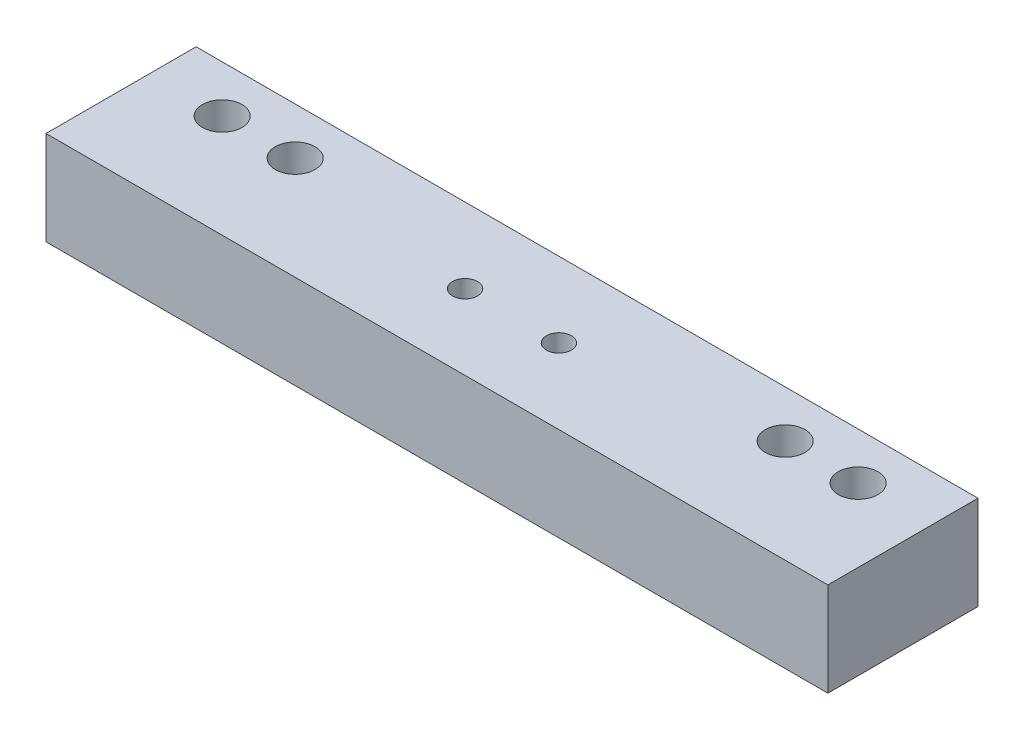
SolidWorks part; units mm, degrees
ref_plane "Front" through (0, 0, 0) normal (0, 0, 1) x (1, 0, 0)
ref_plane "Top" through (0, 0, 0) normal (0, 1, 0) x (1, 0, 0)
ref_plane "Right" through (0, 0, 0) normal (1, 0, 0) x (0, 0, -1)
sketch "Sketch1" plane through (0, 0, 0) normal (0, 1, 0) x (1, 0, 0)
  line L1 (0, 0) -> (125, 0)
  line L2 (0, 0) -> (0, 24)
  line L3 (0, 24) -> (125, 24)
  line L4 (125, 0) -> (125, 24)
  dimension "D1" = 125
  dimension "D2" = 24
extrude "Boss-Extrude1" add sketch "Sketch1" along normal blind 15
ref_plane "Plane1" through (62.5, 0, 0) normal (-1, 0, 0) x (0, 0, 1)
ref_plane "Plane2" through (0, 0, -12) normal (0, 0, 1) x (1, 0, 0)
sketch "Sketch2" plane through (0, 15, 0) normal (0, 1, 0) x (1, 0, 0)
  line L1 (125, 0) -> (125, 24) construction
  line L2 (125, 24) -> (0, 24) construction
  circle A0 centre (113.3333, 16.5) radius 3.175
  circle A2 centre (101.6667, 16.5) radius 3.175
  point P8 (0, 0)
  dimension "D1" = 6.35
  dimension "D4" = 6.35
  dimension "D2" = 11.6667
  dimension "D3" = 7.5
  dimension "D5" = 11.6667
extrude "Cut-Extrude1" cut sketch "Sketch2" against normal through all and the other way through all
mirror "Mirror1" about plane through (62.5, 0, 0) normal (-1, 0, 0) of "Cut-Extrude1"
sketch "Sketch5" plane through (0, 15, 0) normal (0, 1, 0) x (1, 0, 0)
  line L0 (-8.25, 12) -> (8.25, 12) construction
  line L1 (125, 0) -> (125, 24) construction
  circle A0 centre (70, 12) radius 2
  dimension "D1" = 4
  dimension "D2" = 55
extrude "Cut-Extrude2" cut sketch "Sketch5" against normal through all
mirror "Mirror2" about plane through (62.5, 0, 0) normal (-1, 0, 0) of "Cut-Extrude2"
